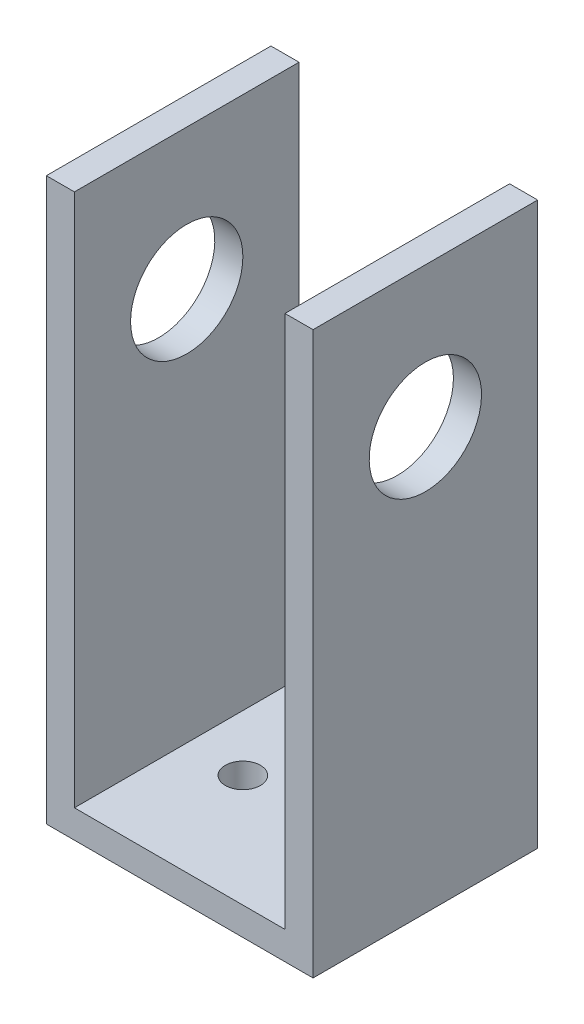
SolidWorks part; units mm, degrees
ref_plane "前视基准面" through (0, 0, 0) normal (0, 0, 1) x (1, 0, 0)
ref_plane "上视基准面" through (0, 0, 0) normal (0, 1, 0) x (1, 0, 0)
ref_plane "右视基准面" through (0, 0, 0) normal (1, 0, 0) x (0, 0, -1)
sketch "草图1" plane through (0, 0, 0) normal (0, 0, 1) x (1, 0, 0)
  line L0 (0, 0) -> (2, 0)
  line L1 (2, 2) -> (2, 40)
  line L2 (2, 40) -> (0, 40)
  line L3 (0, 40) -> (0, 0)
  line L4 (2, 0) -> (17, 0)
  line L5 (17, 2) -> (17, 40)
  line L6 (17, 40) -> (19, 40)
  line L7 (19, 40) -> (19, 0)
  line L8 (19, 0) -> (17, 0)
  line L9 (2, 2) -> (17, 2)
  dimension "D1" = 40
  dimension "D2" = 40
  dimension "D3" = 2
  dimension "D4" = 2
  dimension "D5" = 2
  dimension "D6" = 15
extrude "凸台-拉伸1" add sketch "草图1" along normal blind 40
sketch "草图2" plane through (19, 0, 0) normal (1, 0, 0) x (0, 0, -1)
  line L2 (-40, 0) -> (0, 0) construction
  line L3 (-40, 0) -> (-40, 40) construction
  circle A0 centre (-32, 30) radius 4
  dimension "D1" = 30
  dimension "D2" = 8
extrude "切除-拉伸1" cut sketch "草图2" against normal through all
sketch "草图5" plane through (0, 0, 0) normal (-1, 0, 0) x (0, 0, 1)
  line L0 (40, 0) -> (0, 0) construction
  line L1 (0, 40) -> (24, 40)
  line L2 (0, 40) -> (0, 0)
  line L3 (0, 0) -> (24, 0)
  line L4 (24, 40) -> (24, 0)
  circle A0 centre (32, 30) radius 4 construction
  dimension "D1" = 8
extrude "切除-拉伸4" cut sketch "草图5" against normal through all
sketch "草图6" plane through (0, 0, 0) normal (0, -1, 0) x (1, 0, 0)
  line L0 (9.5, 40) -> (9.5, 24) construction
  line L1 (0, 40) -> (19, 40) construction
  line L2 (19, 24) -> (0, 24) construction
  line L3 (0, 32) -> (19, 32) construction
  line L4 (0, 40) -> (0, 24) construction
  line L5 (19, 40) -> (19, 24) construction
  circle A0 centre (13, 32) radius 1.25
  circle A1 centre (6, 32) radius 1.25
  dimension "D1" = 2.5
  dimension "D2" = 3.5
extrude "切除-拉伸5" cut sketch "草图6" against normal through all
